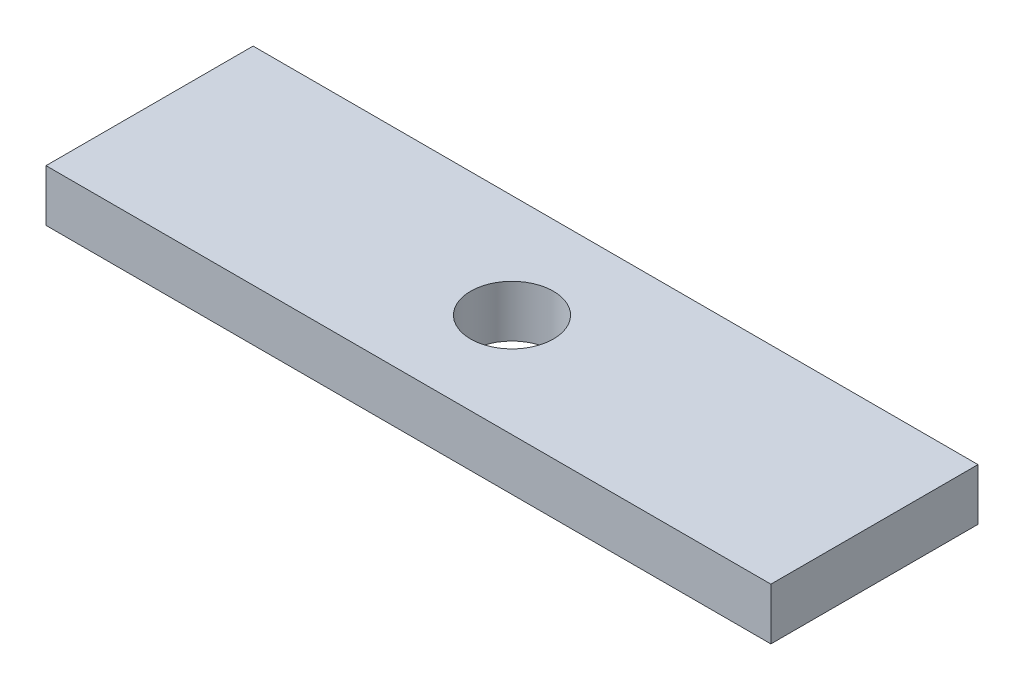
SolidWorks part; units mm, degrees
material "ASTM A36 Steel"
ref_plane "Front Plane" through (0, 0, 0) normal (0, 0, 1) x (1, 0, 0)
ref_plane "Top Plane" through (0, 0, 0) normal (0, 1, 0) x (1, 0, 0)
ref_plane "Right Plane" through (0, 0, 0) normal (1, 0, 0) x (0, 0, -1)
sketch "Sketch1" plane through (0, 0, 0) normal (0, 1, 0) x (1, 0, 0)
  line L1 (-70, 20) -> (70, 20)
  line L2 (-70, 20) -> (-70, -20)
  line L3 (-70, -20) -> (70, -20)
  line L4 (70, 20) -> (70, -20)
  line L5 (-70, 20) -> (70, -20) construction
  line L6 (-70, -20) -> (70, 20) construction
  circle A0 centre (0, 0) radius 8
  point P0 (0, 0)
  dimension "D3" = 16
  dimension "D1" = 140
  dimension "D2" = 40
extrude "Boss-Extrude1" add sketch "Sketch1" along normal mid plane 10
